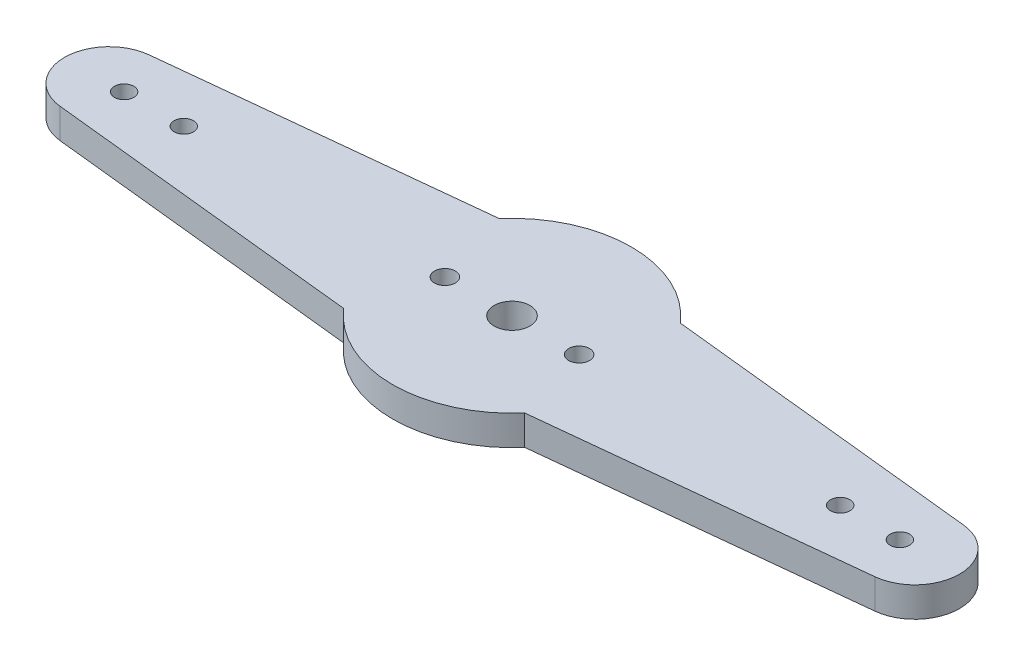
SolidWorks part; units mm, degrees
ref_plane "Plan de face" through (0, 0, 0) normal (0, 0, 1) x (1, 0, 0)
ref_plane "Plan de dessus" through (0, 0, 0) normal (0, 1, 0) x (1, 0, 0)
ref_plane "Plan de droite" through (0, 0, 0) normal (1, 0, 0) x (0, 0, -1)
sketch "Esquisse1" plane through (0, 0, 0) normal (0, 1, 0) x (1, 0, 0)
  line L0 (-30.325, 26.0844) -> (-136.5679, 14.9178)
  line L1 (-150, 0) -> (0, 0) construction
  line L2 (0, 0) -> (0, 40) construction
  line L3 (-150, 0) -> (0, 0)
  line L4 (0, 0) -> (0, 40)
  arc A0 (0, 40) -> (-30.325, 26.0844) centre (0, 0) ccw
  arc A1 (-136.5679, 14.9178) -> (-150, 0) centre (-135, 0) ccw
  point P6 (-132.4828, 3.4434)
  point P9 (0, 0)
  point P10 (0, 0)
  point P11 (-27.9101, 30.3036)
  point P12 (-37.8932, 27.8573)
  point P13 (0, 0)
  dimension "D3" = 15
  dimension "D1" = 150
  dimension "D2" = 40
  dimension "D4" = 6
extrude "Boss.-Extru.1" add sketch "Esquisse1" along normal blind 10
mirror "Symétrie1" about plane through (-150, 10, 0) normal (0, 0, -1) of "Boss.-Extru.1"
mirror "Symétrie8" about plane through (0, 0, 0) normal (1, 0, 0) of "Boss.-Extru.1", "Symétrie1"
sketch "Esquisse2" plane through (0, 10, 0) normal (0, 1, 0) x (1, 0, 0)
  line L0 (-22.5, 0) -> (22.5, 0) construction
  circle A0 centre (-22.5, 0) radius 3.5
  circle A1 centre (22.5, 0) radius 3.5
  circle A2 centre (0, 0) radius 6
  circle A3 centre (-110, 0) radius 3.25
  circle A4 centre (-130, 0) radius 3.25
  circle A5 centre (110, 0) radius 3.25
  circle A6 centre (130, 0) radius 3.25
  point P15 (0, 0)
  point P16 (0, 0)
  point P17 (0, 0)
  point P18 (0, 0)
  point P19 (0, 0)
  dimension "D2" = 7
  dimension "D3" = 7
  dimension "D4" = 12
  dimension "D5" = 6.5
  dimension "D6" = 6.5
  dimension "D7" = 6.5
  dimension "D8" = 6.5
  dimension "D1" = 45
  dimension "D9" = 110
  dimension "D10" = 20
  dimension "D11" = 20
  dimension "D12" = 110
extrude "Enlèv. mat.-Extru.1" cut sketch "Esquisse2" against normal blind 10
